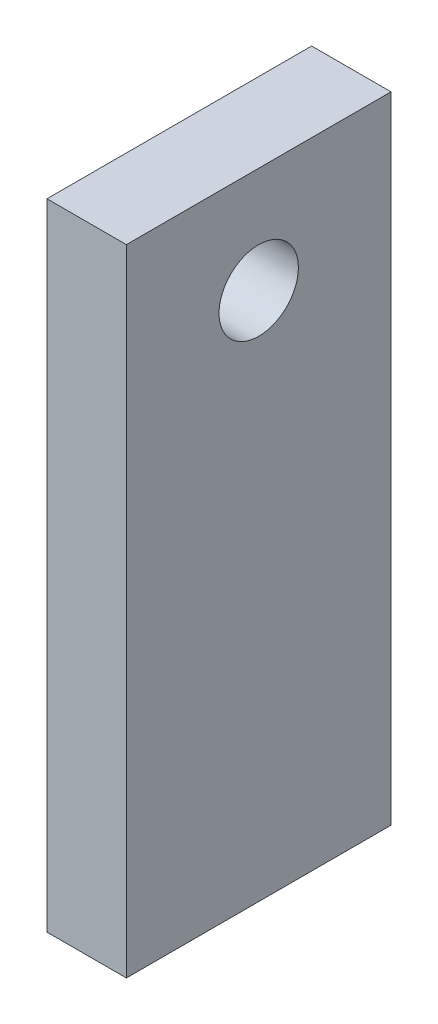
SolidWorks part; units mm, degrees
ref_plane "Front Plane" through (0, 0, 0) normal (0, 0, 1) x (1, 0, 0)
ref_plane "Top Plane" through (0, 0, 0) normal (0, 1, 0) x (1, 0, 0)
ref_plane "Right Plane" through (0, 0, 0) normal (1, 0, 0) x (0, 0, -1)
sketch "Sketch1" plane through (0, 0, 0) normal (1, 0, 0) x (0, 0, -1)
  line L1 (-25, 60) -> (25, 60)
  line L2 (-25, 60) -> (-25, -60)
  line L3 (-25, -60) -> (25, -60)
  line L4 (25, 60) -> (25, -60)
  line L5 (-25, 60) -> (25, -60) construction
  line L6 (-25, -60) -> (25, 60) construction
  point P1 (0, 0)
  dimension "D1" = 120
  dimension "D2" = 50
extrude "Boss-Extrude1" add sketch "Sketch1" along normal blind 15
sketch "Sketch2" plane through (15, 0, 0) normal (1, 0, 0) x (0, 0, -1)
  line L0 (0, 60) -> (0, -60) construction
  line L1 (25, 60) -> (-25, 60) construction
  line L2 (-25, -60) -> (25, -60) construction
  line L3 (-25, 40) -> (25, 40) construction
  line L4 (-25, 60) -> (-25, -60) construction
  line L5 (25, -60) -> (25, 60) construction
  circle A0 centre (0, 40) radius 7.5
  dimension "D1" = 20
  dimension "D2" = 15
extrude "Cut-Extrude1" cut sketch "Sketch2" against normal up to next
